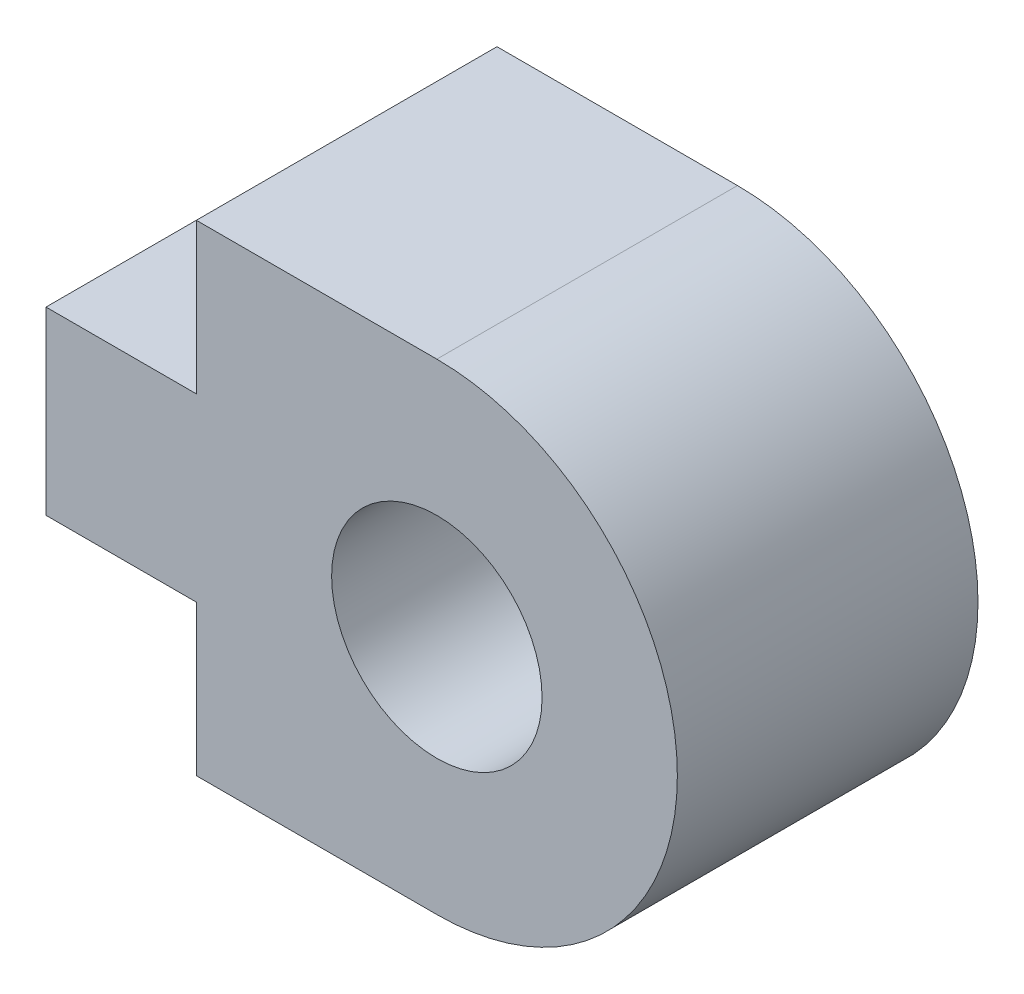
SolidWorks part; units mm, degrees
material "PP Copolymer"
ref_plane "Alzado" through (0, 0, 0) normal (0, 0, 1) x (1, 0, 0)
ref_plane "Planta" through (0, 0, 0) normal (0, 1, 0) x (1, 0, 0)
ref_plane "Vista lateral" through (0, 0, 0) normal (1, 0, 0) x (0, 0, -1)
sketch "Croquis1" plane through (0, 0, 0) normal (0, 0, 1) x (1, 0, 0)
  line L0 (0, -4) -> (-4, -4)
  line L1 (0, 4) -> (-4, 4)
  line L2 (-4, -4) -> (-4, -1.5)
  line L3 (-4, 1.5) -> (-6.5, 1.5)
  line L4 (-6.5, 1.5) -> (-6.5, -1.5)
  line L5 (-6.5, -1.5) -> (-4, -1.5)
  line L6 (-4, 1.5) -> (-4, 4)
  line L7 (-6.5, 0) -> (0, 0) construction
  circle A0 centre (0, 0) radius 1.75
  arc A1 (0, -4) -> (0, 4) centre (0, 0) ccw
  dimension "D2" = 3.5
  dimension "D1" = 8
  dimension "D3" = 4
  dimension "D4" = 3
  dimension "D5" = 2.5
extrude "Saliente-Extruir1" add sketch "Croquis1" along normal mid plane 5
